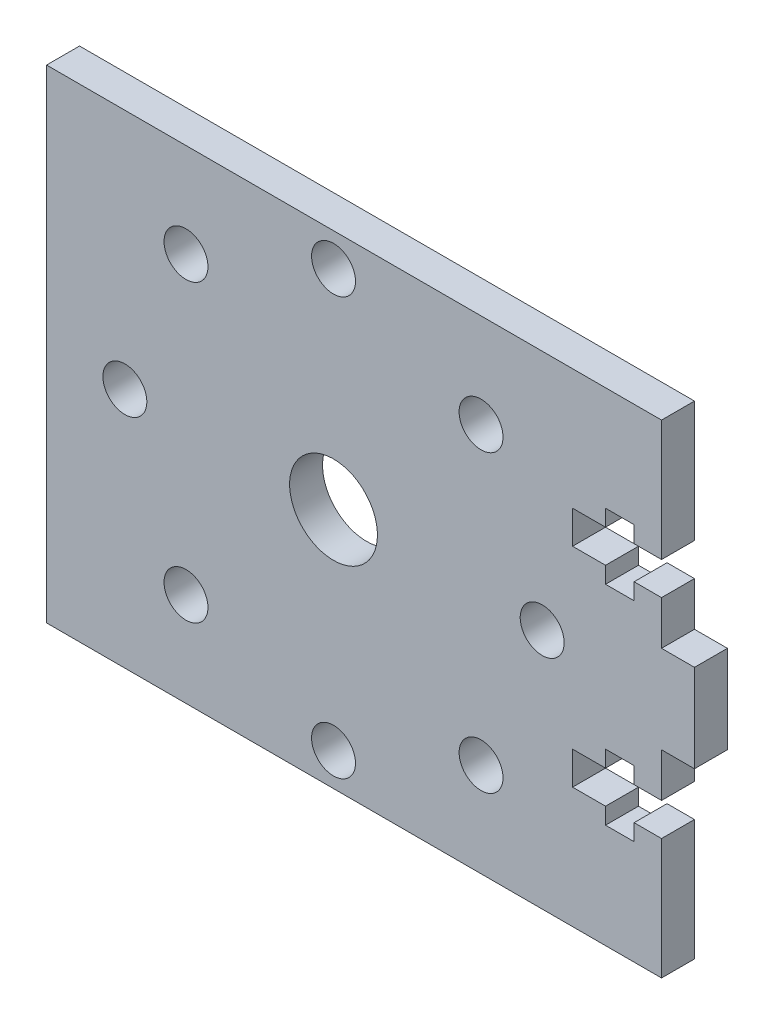
SolidWorks part; units mm, degrees
ref_plane "前视基准面" through (0, 0, 0) normal (0, 0, 1) x (1, 0, 0)
ref_plane "上视基准面" through (0, 0, 0) normal (0, 1, 0) x (1, 0, 0)
ref_plane "右视基准面" through (0, 0, 0) normal (1, 0, 0) x (0, 0, -1)
sketch "草图1" plane through (0, 0, 0) normal (0, 0, 1) x (1, 0, 0)
  line L2 (27.3701, 11) -> (27.3701, 12.5)
  line L3 (27.3701, 8) -> (27.3701, 6.5)
  line L4 (29.8701, 8) -> (27.3701, 8)
  line L5 (27.3701, 12.5) -> (24.7701, 12.5)
  line L6 (24.7701, 12.5) -> (24.7701, 11)
  line L7 (24.7701, 11) -> (21.7701, 11)
  line L8 (21.7701, 8) -> (21.7701, 11)
  line L9 (24.7701, 8) -> (21.7701, 8)
  line L10 (24.7701, 6.5) -> (24.7701, 8)
  line L11 (27.3701, 6.5) -> (24.7701, 6.5)
  line L12 (27.3701, 11) -> (29.8701, 11)
  line L30 (32.8701, 0) -> (32.8701, 4)
  line L31 (32.8701, 0) -> (32.8701, -4)
  line L32 (32.8701, 4) -> (29.8701, 4)
  line L33 (29.8701, 4) -> (29.8701, 8)
  line L34 (32.8701, -4) -> (29.8701, -4)
  line L35 (29.8701, -4) -> (29.8701, -8)
  line L36 (27.3701, -11) -> (29.8701, -11)
  line L37 (27.3701, -6.5) -> (24.7701, -6.5)
  line L38 (24.7701, -6.5) -> (24.7701, -8)
  line L39 (24.7701, -8) -> (21.7701, -8)
  line L40 (21.7701, -8) -> (21.7701, -11)
  line L41 (24.7701, -11) -> (21.7701, -11)
  line L42 (24.7701, -12.5) -> (24.7701, -11)
  line L43 (27.3701, -12.5) -> (24.7701, -12.5)
  line L44 (29.8701, -8) -> (27.3701, -8)
  line L45 (27.3701, -8) -> (27.3701, -6.5)
  line L46 (27.3701, -11) -> (27.3701, -12.5)
  line L47 (29.8701, 11) -> (29.8701, 22)
  line L48 (29.8701, 22) -> (-26.1299, 22)
  line L49 (29.8701, -11) -> (29.8701, -22)
  line L50 (29.8701, -22) -> (-26.1299, -22)
  line L51 (-26.1299, 22) -> (-26.1299, -22)
  circle A0 centre (0, 0) radius 19 construction
  circle A1 centre (0, 0) radius 4
  circle A2 centre (0, -19) radius 2
  circle A3 centre (-13.435, -13.435) radius 2
  circle A4 centre (-19, 0) radius 2
  circle A5 centre (-13.435, 13.435) radius 2
  circle A6 centre (0, 19) radius 2
  circle A7 centre (13.435, 13.435) radius 2
  circle A8 centre (19, 0) radius 2
  circle A9 centre (13.435, -13.435) radius 2
  circle A10 centre (0, 0) radius 80 construction
  dimension "D1" = 8
extrude "凸台-拉伸1" add sketch "草图1" along normal blind 3
sketch "草图2" plane through (29.8701, 0, 0) normal (1, 0, 0) x (0, 0, -1)
  line L0 (-1.5, -8) -> (-1.5, -11)
  line L1 (-3, -8) -> (0, -8) construction
  line L2 (-3, -11) -> (0, -11) construction
  circle A0 centre (-1.5, -9.5) radius 1.5
